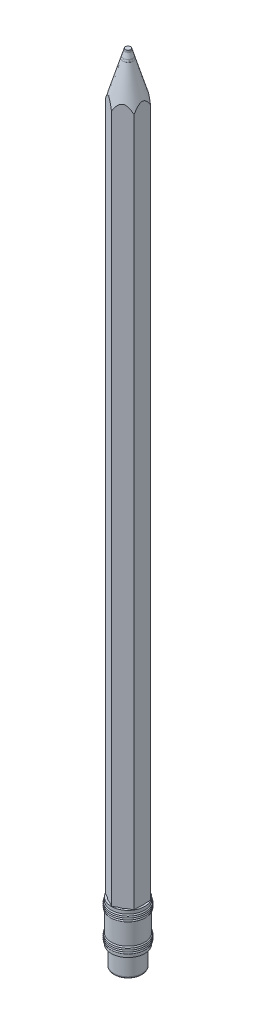
SolidWorks part; units mm, degrees
ref_plane "Front Plane" through (0, 0, 0) normal (0, 0, 1) x (1, 0, 0)
ref_plane "Top Plane" through (0, 0, 0) normal (0, 1, 0) x (1, 0, 0)
ref_plane "Right Plane" through (0, 0, 0) normal (1, 0, 0) x (0, 0, -1)
sketch "Sketch4" plane through (0, 0, 0) normal (0, 1, 0) x (1, 0, 0)
  circle A0 centre (0, 0) radius 1.275
  dimension "D1" = 2.55
extrude "Boss-Extrude2" add sketch "Sketch4" along normal blind 185
sketch "Sketch5" plane through (0, 185, 0) normal (0, 1, 0) x (1, 0, 0)
  line L1 (0, 4.0415) -> (-3.5, 2.0207)
  line L2 (-3.5, 2.0207) -> (-3.5, -2.0207)
  line L3 (-3.5, -2.0207) -> (0, -4.0415)
  line L4 (0, -4.0415) -> (3.5, -2.0207)
  line L5 (3.5, -2.0207) -> (3.5, 2.0207)
  line L6 (3.5, 2.0207) -> (0, 4.0415)
  circle A0 centre (0, 0) radius 3.5 construction
  dimension "D1" = 7
extrude "Boss-Extrude3" add sketch "Sketch5" against normal blind 185 separate body
sketch "Sketch11" plane through (0, 0, 0) normal (0, -1, 0) x (1, 0, 0)
  circle A0 centre (0, 0) radius 3.5
  dimension "D1" = 7
extrude "Boss-Extrude4" add sketch "Sketch11" along normal blind 10 separate body
fillet "Fillet1" radius 0.5 1 edges at (0, -10, -3.5)
sketch "Sketch15" plane through (0, 0, 0) normal (0, 0, 1) x (1, 0, 0)
  line L0 (0, -9.917) -> (0, 0) construction
  line L1 (-4.1, -5) -> (-4.1, -4.2)
  line L2 (-4.1, -5) -> (-3.6, -5)
  line L3 (-4.1, -5) -> (-4.1, 5) construction
  line L4 (-4.1, 5) -> (-3.6, 5)
  line L5 (-3.6, -5) -> (-3.6, 5)
  line L6 (-4.1, -2.6) -> (-4.1, 2.6)
  line L7 (-4.1, 4.2) -> (-4.1, 5)
  line L9 (0, 0) -> (-10.2387, 0) construction
  arc A0 (-4.1, 4.2) -> (-4.1, 3.8) centre (-4.1, 4) ccw
  arc A1 (-4.1, 3.8) -> (-4.1, 3.4) centre (-4.1, 3.6) ccw
  arc A2 (-4.1, 3.4) -> (-4.1, 3) centre (-4.1, 3.2) ccw
  arc A3 (-4.1, 3) -> (-4.1, 2.6) centre (-4.1, 2.8) ccw
  arc A4 (-4.1, -3) -> (-4.1, -2.6) centre (-4.1, -2.8) cw
  arc A5 (-4.1, -3.4) -> (-4.1, -3) centre (-4.1, -3.2) cw
  arc A6 (-4.1, -3.8) -> (-4.1, -3.4) centre (-4.1, -3.6) cw
  arc A7 (-4.1, -4.2) -> (-4.1, -3.8) centre (-4.1, -4) cw
  dimension "D5" = 0.4
  dimension "D1" = 4.1
  dimension "D2" = 0.5
  dimension "D3" = 10
  dimension "D4" = 5
  dimension "D6" = 1
  dimension "D7" = 4
revolve "Revolve1" add sketch "Sketch15" angle 360 about L0
sketch "Sketch17" plane through (0, 0, 0) normal (0, 0, 1) x (1, 0, 0)
  line L6 (-0.5, 185.4634) -> (-5, 185.4634)
  line L7 (-5, 185.4634) -> (-5, 170.4634)
  line L8 (-5, 170.4634) -> (-0.5, 185.4634)
  line L9 (0, 0) -> (0, 185) construction
  point P2 (0, 0)
  point P8 (-4.5004, 174.5427)
  point P9 (-5, 185.4634)
  dimension "D1" = 185
  dimension "D2" = 15
  dimension "D3" = 0.5
  dimension "D4" = 5
revolve "Cut-Revolve1" cut sketch "Sketch17" angle 360 about L9
sketch "Sketch20" plane through (0, 185, 0) normal (0, 1, 0) x (1, 0, 0)
  circle A0 centre (0, 0) radius 0.639
